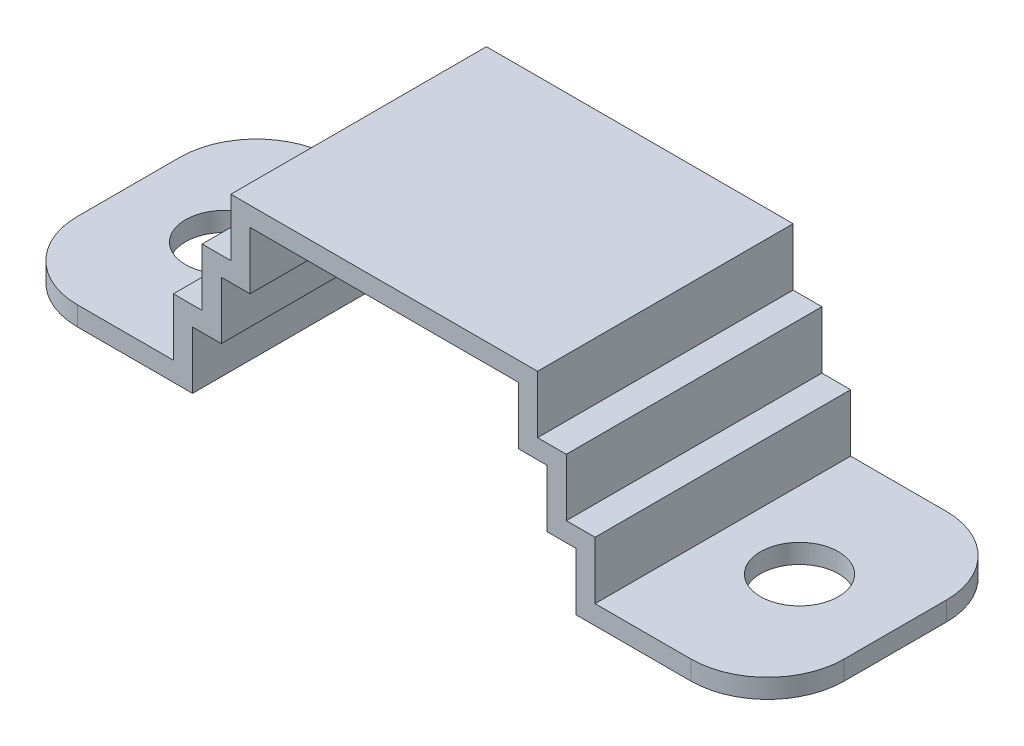
SolidWorks part; units mm, degrees
ref_plane "Front Plane" through (0, 0, 0) normal (0, 0, 1) x (1, 0, 0)
ref_plane "Top Plane" through (0, 0, 0) normal (0, 1, 0) x (1, 0, 0)
ref_plane "Right Plane" through (0, 0, 0) normal (1, 0, 0) x (0, 0, -1)
sketch "Sketch1" plane through (0, 0, 0) normal (0, 0, 1) x (1, 0, 0)
  line L0 (-60, 0) -> (-30, 0)
  line L1 (-30, 0) -> (-30, 9)
  line L2 (-30, 9) -> (-25.5, 9)
  line L3 (-25.5, 9) -> (-25.5, 18)
  line L4 (-25.5, 18) -> (-21, 18)
  line L5 (-21, 18) -> (-21, 27)
  line L6 (-21, 27) -> (0, 27)
  circle A0 centre (0, 0) radius 27.05
  dimension "D1" = 54.1
  dimension "D2" = 9
  dimension "D3" = 30
  dimension "D4" = 4.5
  dimension "D5" = 30
  dimension "D6" = 21
extrude "Extrude-Thin1" add sketch "Sketch1" against normal mid plane 40 thin contours L0 L1 L2 L3 L4 L5 L6
mirror "Mirror1" about plane through (0, 30, -20) normal (-1, 0, 0) of "Extrude-Thin1"
sketch "Sketch4" plane through (0, 3, 0) normal (0, 1, 0) x (1, 0, 0)
  circle A0 centre (-45, 0) radius 6.1
  point P2 (0, 0)
  dimension "D1" = 12.2
  dimension "D2" = 45
extrude "Cut-Extrude3" cut sketch "Sketch4" against normal through all
mirror "Mirror3" about plane through (0, 0, 0) normal (1, 0, 0) of "Cut-Extrude3"
fillet "Fillet1" radius 12 4 edges at (-60, 1.5, 20) (-60, 1.5, -20) (60, 1.5, -20) (60, 1.5, 20)
